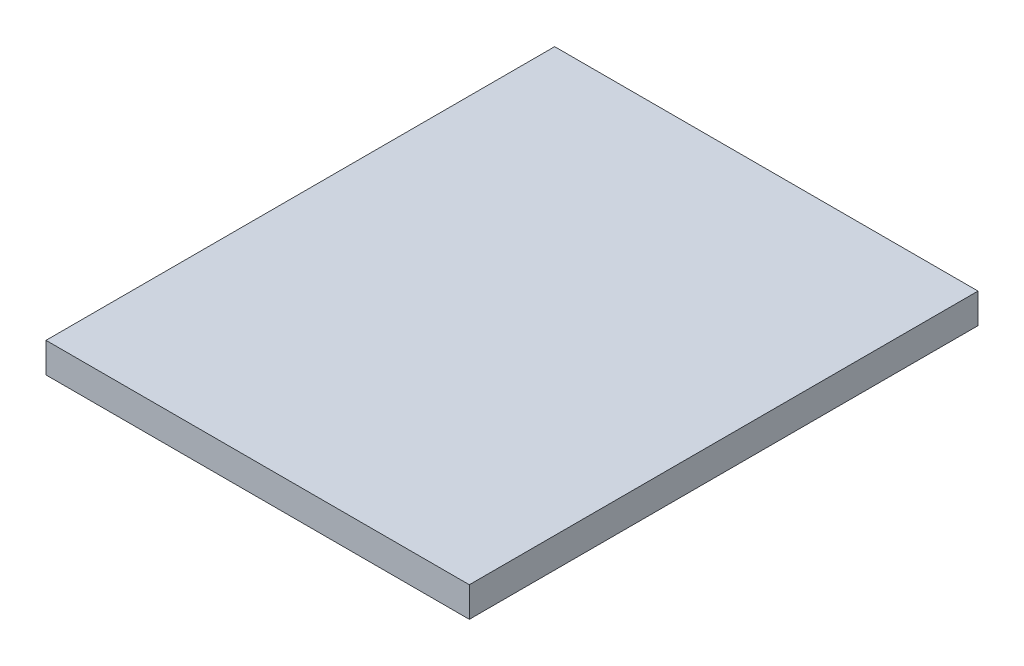
SolidWorks part; units mm, degrees
material "Acrylic (Medium-high impact)"
ref_plane "Front Plane" through (0, 0, 0) normal (0, 0, 1) x (1, 0, 0)
ref_plane "Top Plane" through (0, 0, 0) normal (0, 1, 0) x (1, 0, 0)
ref_plane "Right Plane" through (0, 0, 0) normal (1, 0, 0) x (0, 0, -1)
sketch "Sketch1" plane through (0, 0, 0) normal (0, 1, 0) x (1, 0, 0)
  line L1 (-43.815, -47.5) -> (43.815, -47.5) construction
  line L2 (-43.815, -47.5) -> (-43.815, 47.5) construction
  line L3 (-43.815, 47.5) -> (43.815, 47.5) construction
  line L4 (43.815, -47.5) -> (43.815, 47.5) construction
  line L5 (-43.815, -47.5) -> (43.815, 47.5) construction
  line L6 (-43.815, 47.5) -> (43.815, -47.5) construction
  line L8 (44.815, -53.85) -> (-44.815, -53.85)
  line L9 (44.815, -53.85) -> (44.815, 53.85)
  line L10 (44.815, 53.85) -> (-44.815, 53.85)
  line L11 (-44.815, -53.85) -> (-44.815, 53.85)
  line L12 (44.815, -53.85) -> (-44.815, 53.85) construction
  line L13 (44.815, 53.85) -> (-44.815, -53.85) construction
  point P0 (0, 0)
  point P6 (0, 0)
  dimension "D1" = 95
  dimension "D2" = 87.63
  dimension "D3" = 6.35
  dimension "D4" = 1
extrude "Boss-Extrude1" add sketch "Sketch1" along normal blind 6.35
